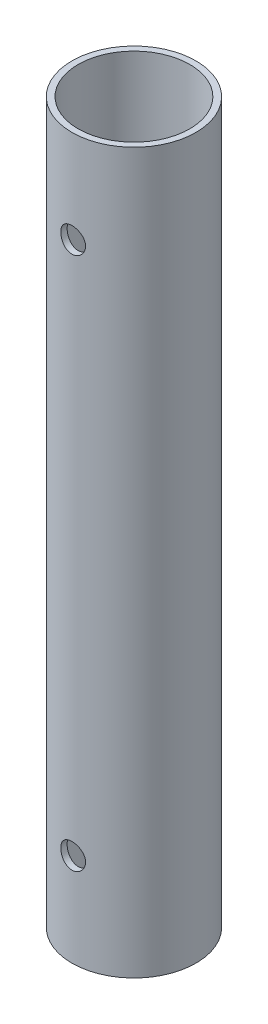
SolidWorks part; units mm, degrees
ref_plane "Alzado" through (0, 0, 0) normal (0, 0, 1) x (1, 0, 0)
ref_plane "Planta" through (0, 0, 0) normal (0, 1, 0) x (1, 0, 0)
ref_plane "Vista lateral" through (0, 0, 0) normal (1, 0, 0) x (0, 0, -1)
sketch "Croquis1" plane through (0, 0, 0) normal (0, 1, 0) x (1, 0, 0)
  circle A0 centre (0, 0) radius 10
  circle A1 centre (0, 0) radius 9
  dimension "D1" = 20
  dimension "D2" = 18
extrude "Saliente-Extruir1" add sketch "Croquis1" along normal mid plane 116
sketch "Croquis2" plane through (0, 0, 0) normal (0, 0, 1) x (1, 0, 0)
  line L0 (0, 58) -> (0, 0) construction
  line L1 (10, 58) -> (-10, 58) construction
  line L2 (-10, -58) -> (10, -58) construction
  circle A0 centre (0, -43) radius 2
  circle A1 centre (0, 43) radius 2
  dimension "D1" = 4
  dimension "D3" = 4
  dimension "D2" = 15
  dimension "D4" = 15
extrude "Cortar-Extruir1" cut sketch "Croquis2" against normal through all both and the other way through all
